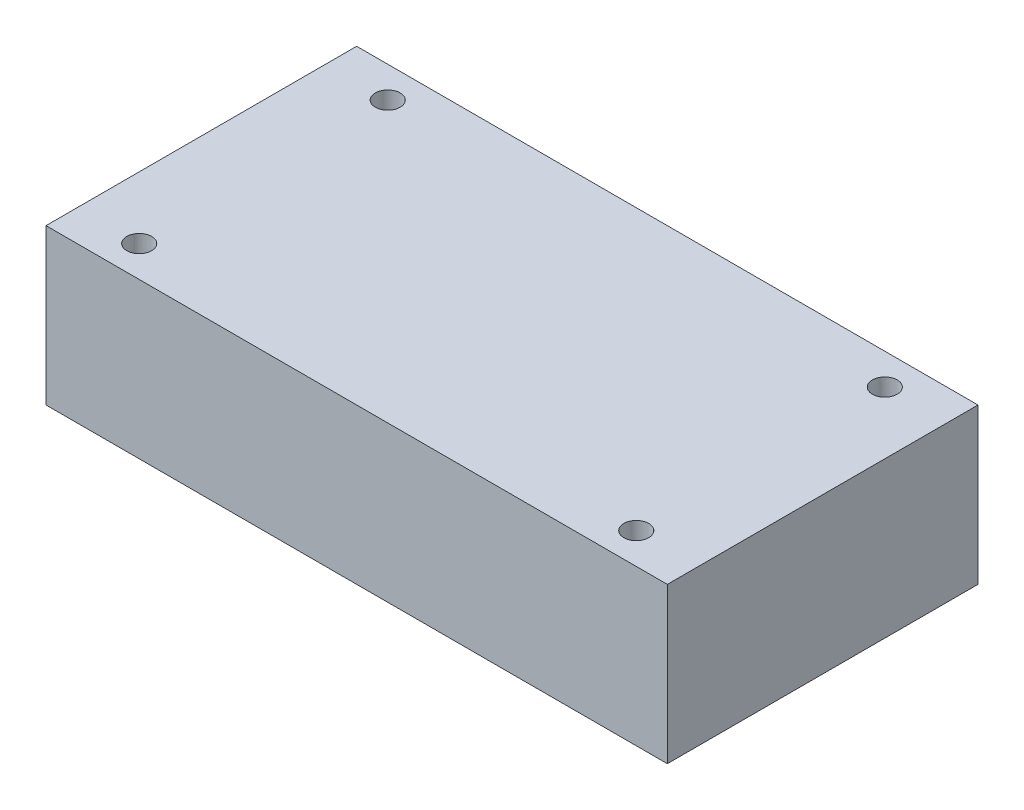
SolidWorks part; units mm, degrees
ref_plane "前视基准面" through (0, 0, 0) normal (0, 0, 1) x (1, 0, 0)
ref_plane "上视基准面" through (0, 0, 0) normal (0, 1, 0) x (1, 0, 0)
ref_plane "右视基准面" through (0, 0, 0) normal (1, 0, 0) x (0, 0, -1)
sketch "草图1" plane through (0, 0, 0) normal (0, 1, 0) x (1, 0, 0)
  line L1 (0, 0) -> (100, 0)
  line L2 (0, 0) -> (0, 50)
  line L3 (0, 50) -> (100, 50)
  line L4 (100, 0) -> (100, 50)
  point P4 (0, 0)
  point P5 (0, 0)
  point P6 (0, 0)
extrude "凸台-拉伸1" add sketch "草图1" along normal blind 25
sketch "草图2" plane through (0, 25, 0) normal (0, 1, 0) x (1, 0, 0)
  circle A0 centre (10, 5) radius 2
  circle A1 centre (90, 5) radius 2
  circle A2 centre (10, 45) radius 2
  circle A3 centre (90, 45) radius 2
extrude "切除-拉伸1" cut sketch "草图2" against normal through all
